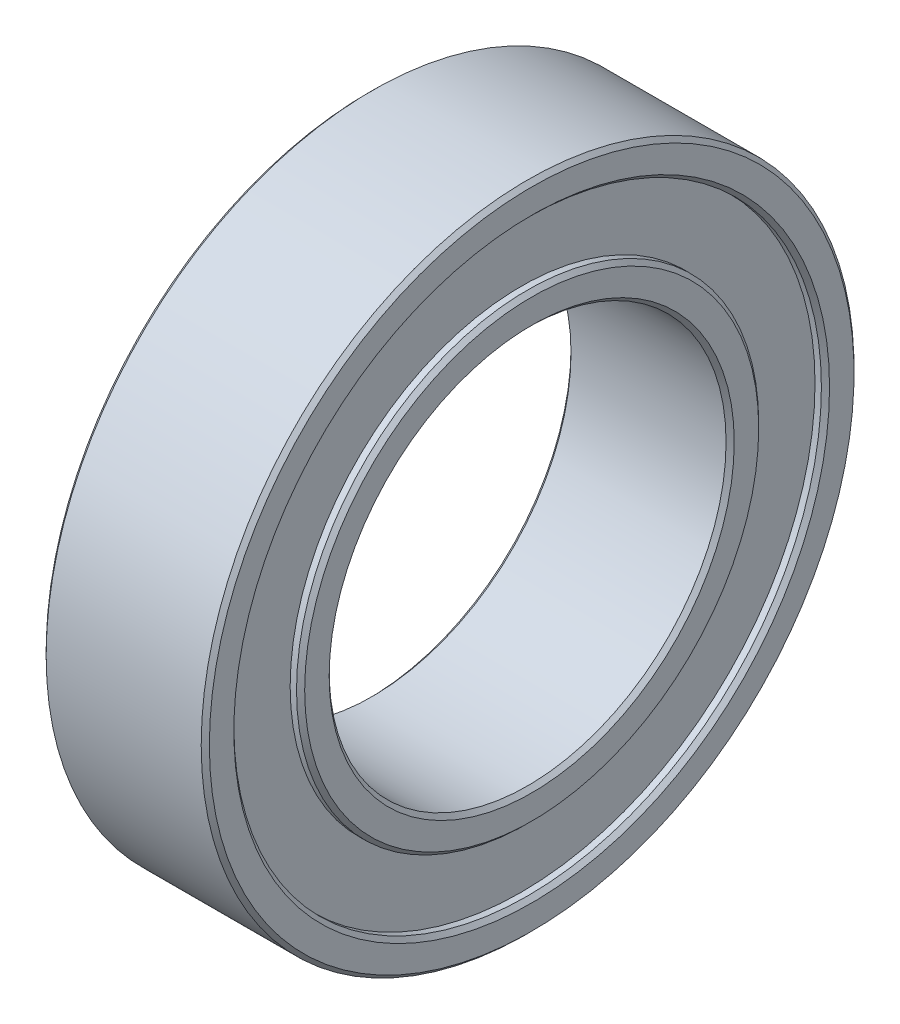
SolidWorks part; units mm, degrees
material "AISI 316 Annealed Stainless Steel Bar (SS)"
ref_plane "Front Plane" through (0, 0, 0) normal (0, 0, 1) x (1, 0, 0)
ref_plane "Top Plane" through (0, 0, 0) normal (0, 1, 0) x (1, 0, 0)
ref_plane "Right Plane" through (0, 0, 0) normal (1, 0, 0) x (0, 0, -1)
sketch "Sketch1" plane through (0, 0, 0) normal (1, 0, 0) x (0, 0, -1)
  circle A1 centre (0, 0) radius 4.826
  circle A2 centre (0, 0) radius 7.9375
  circle A3 centre (0, 0) radius 7.1438
  circle A4 centre (0, 0) radius 5.6197
  dimension "D1" = 9.652
  dimension "D2" = 0.7937
  dimension "D3" = 15.875
  dimension "D4" = 0.7937
extrude "Boss-Extrude1" add sketch "Sketch1" along normal mid plane 3.9688 contours A4 A1 | A2 A3
sketch "Sketch2" plane through (0, 0, 0) normal (1, 0, 0) x (0, 0, -1)
  circle A0 centre (0, 0) radius 7.1438 construction
  circle A1 centre (0, 0) radius 5.6197 construction
  circle A2 centre (0, 0) radius 7.1438
  circle A3 centre (0, 0) radius 5.6197
extrude "Boss-Extrude2" add sketch "Sketch2" along normal mid plane 3.4608
chamfer "Chamfer1" distance 0.0992 angle 45 6 edges at (-1.9844, 0, -4.826) (1.9844, 0, -4.826) (-1.9844, 0, -7.9375) (1.9844, 0, -7.9375) (1.9844, 0, -7.1438) (1.9844, 0, -5.6197)
